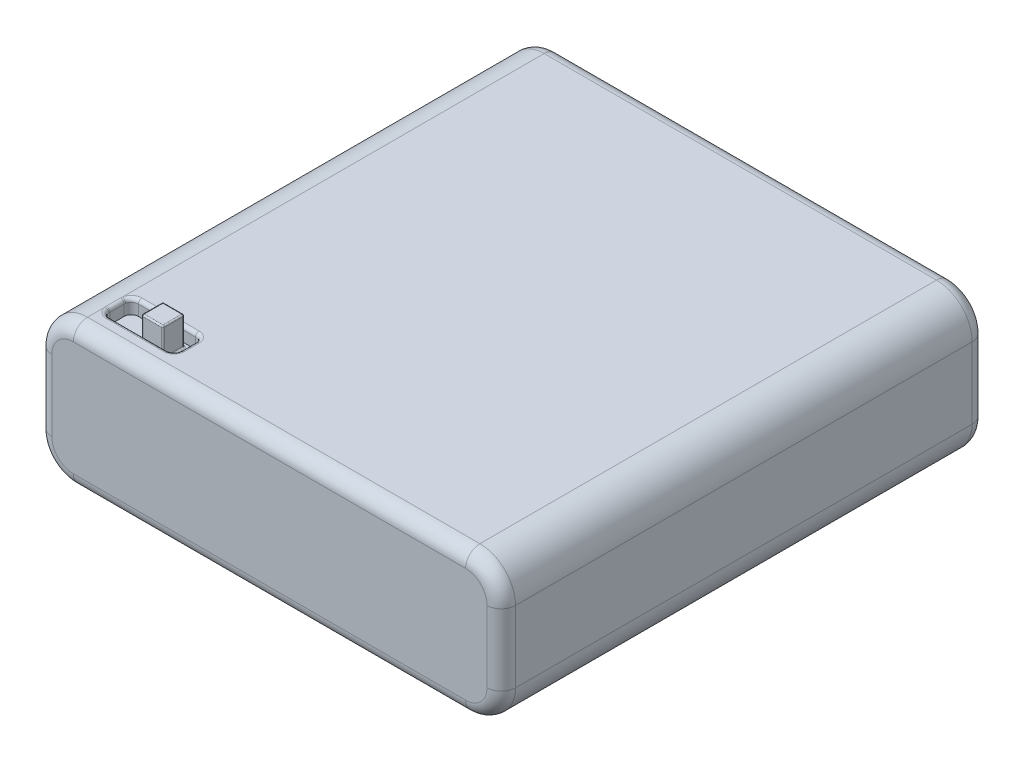
SolidWorks part; units mm, degrees
ref_plane "Front Plane" through (0, 0, 0) normal (0, 0, 1) x (1, 0, 0)
ref_plane "Top Plane" through (0, 0, 0) normal (0, 1, 0) x (1, 0, 0)
ref_plane "Right Plane" through (0, 0, 0) normal (1, 0, 0) x (0, 0, -1)
sketch "Sketch1" plane through (0, 0, 0) normal (0, 1, 0) x (1, 0, 0)
  line L1 (-32.5, 34) -> (32.5, 34)
  line L2 (-32.5, 34) -> (-32.5, -34)
  line L3 (-32.5, -34) -> (32.5, -34)
  line L4 (32.5, 34) -> (32.5, -34)
  line L5 (-32.5, 34) -> (32.5, -34) construction
  line L6 (-32.5, -34) -> (32.5, 34) construction
  point P0 (0, 0)
  dimension "D1" = 68
  dimension "D2" = 65
extrude "Boss-Extrude1" add sketch "Sketch1" along normal blind 20
fillet "Fillet1" radius 5 4 edges at (-32.5, 0, 0) (-32.5, 20, 0) (32.5, 0, 0) (32.5, 20, 0)
fillet "Fillet2" radius 2 16 edges at (31.0355, 1.4645, -34) (32.5, 10, -34) (31.0355, 18.5355, -34) (0, 20, -34) (-31.0355, 18.5355, -34) (-32.5, 10, -34) (-31.0355, 1.4645, -34) (0, 0, -34) (-31.0355, 18.5355, 34) (0, 20, 34) (31.0355, 18.5355, 34) (32.5, 10, 34) (31.0355, 1.4645, 34) (0, 0, 34) (-31.0355, 1.4645, 34) (-32.5, 10, 34)
sketch "Sketch2" plane through (0, 20, 0) normal (0, 1, 0) x (1, 0, 0)
  line L1 (-26.0224, -26.3495) -> (-18.0224, -26.3495)
  line L2 (-27.0224, -27.3495) -> (-27.0224, -29.3495)
  line L3 (-26.0224, -30.3495) -> (-18.0224, -30.3495)
  line L4 (-17.0224, -27.3495) -> (-17.0224, -29.3495)
  line L5 (-27.0224, -26.3495) -> (-17.0224, -30.3495) construction
  line L6 (-27.0224, -30.3495) -> (-17.0224, -26.3495) construction
  arc A0 (-26.0224, -26.3495) -> (-27.0224, -27.3495) centre (-26.0224, -27.3495) ccw
  arc A1 (-27.0224, -29.3495) -> (-26.0224, -30.3495) centre (-26.0224, -29.3495) ccw
  arc A2 (-18.0224, -30.3495) -> (-17.0224, -29.3495) centre (-18.0224, -29.3495) ccw
  arc A3 (-18.0224, -26.3495) -> (-17.0224, -27.3495) centre (-18.0224, -27.3495) cw
  point P0 (-22.0224, -28.3495)
  point P5 (-21.7946, -28.4254)
  point P18 (-22.0224, -28.3495)
  dimension "D3" = 1
  dimension "D1" = 10
  dimension "D2" = 4
extrude "Cut-Extrude1" cut sketch "Sketch2" against normal blind 2
fillet "Fillet3" radius 0.5 8 edges at (-17.3153, 20, 26.6424) (-17.0224, 20, 28.3495) (-17.3153, 20, 30.0566) (-22.0224, 20, 30.3495) (-26.7295, 20, 30.0566) (-27.0224, 20, 28.3495) (-26.7295, 20, 26.6424) (-22.0224, 20, 26.3495)
sketch "Sketch3" plane through (0, 18, 0) normal (0, 1, 0) x (1, 0, 0)
  line L1 (-22.0846, -26.8495) -> (-19.0846, -26.8495)
  line L2 (-22.0846, -26.8495) -> (-22.0846, -29.8495)
  line L3 (-22.0846, -29.8495) -> (-19.0846, -29.8495)
  line L4 (-19.0846, -26.8495) -> (-19.0846, -29.8495)
  line L5 (-22.0846, -26.8495) -> (-19.0846, -29.8495) construction
  line L6 (-22.0846, -29.8495) -> (-19.0846, -26.8495) construction
  point P0 (-20.5846, -28.3495)
  point P5 (0, 0)
  dimension "D1" = 3
extrude "Boss-Extrude2" add sketch "Sketch3" along normal blind 4
fillet "Fillet4" radius 0.2 12 edges at (-19.0846, 18, 28.3495) (-19.0846, 20, 26.8495) (-20.5846, 18, 26.8495) (-22.0846, 20, 26.8495) (-22.0846, 18, 28.3495) (-22.0846, 20, 29.8495) (-19.0846, 20, 29.8495) (-20.5846, 18, 29.8495) (-20.5846, 22, 29.8495) (-22.0846, 22, 28.3495) (-20.5846, 22, 26.8495) (-19.0846, 22, 28.3495)
